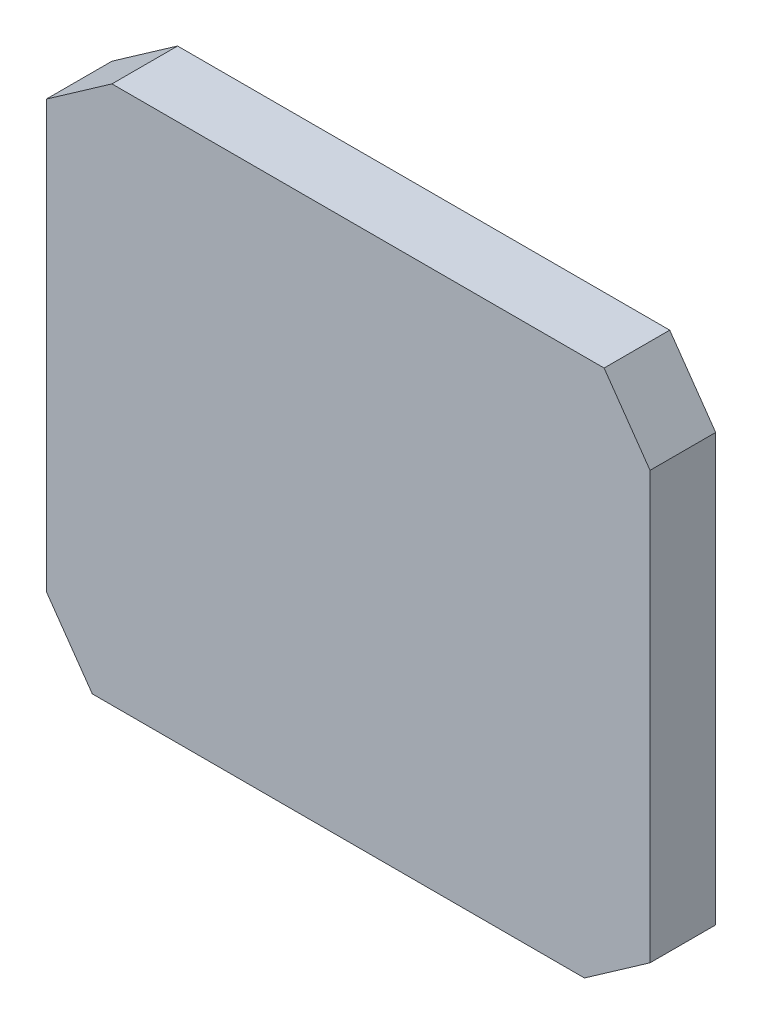
SolidWorks part; units mm, degrees
ref_plane "前视基准面" through (0, 0, 0) normal (0, 0, 1) x (1, 0, 0)
ref_plane "上视基准面" through (0, 0, 0) normal (0, 1, 0) x (1, 0, 0)
ref_plane "右视基准面" through (0, 0, 0) normal (1, 0, 0) x (0, 0, -1)
sketch "草图1" plane through (0, 0, 0) normal (0, 0, 1) x (1, 0, 0)
  line L1 (-92, 82) -> (92, 82)
  line L2 (-92, 82) -> (-92, -82)
  line L3 (-92, -82) -> (92, -82)
  line L4 (92, 82) -> (92, -82)
  line L5 (-92, 82) -> (92, -82) construction
  line L6 (-92, -82) -> (92, 82) construction
  point P0 (0, 0)
  dimension "D1" = 184
  dimension "D2" = 164
extrude "凸台-拉伸1" add sketch "草图1" along normal blind 20
chamfer "倒角1" distance 20 angle 35 4 edges at (92, -82, 10) (-92, -82, 10) (92, 82, 10) (-92, 82, 10)
